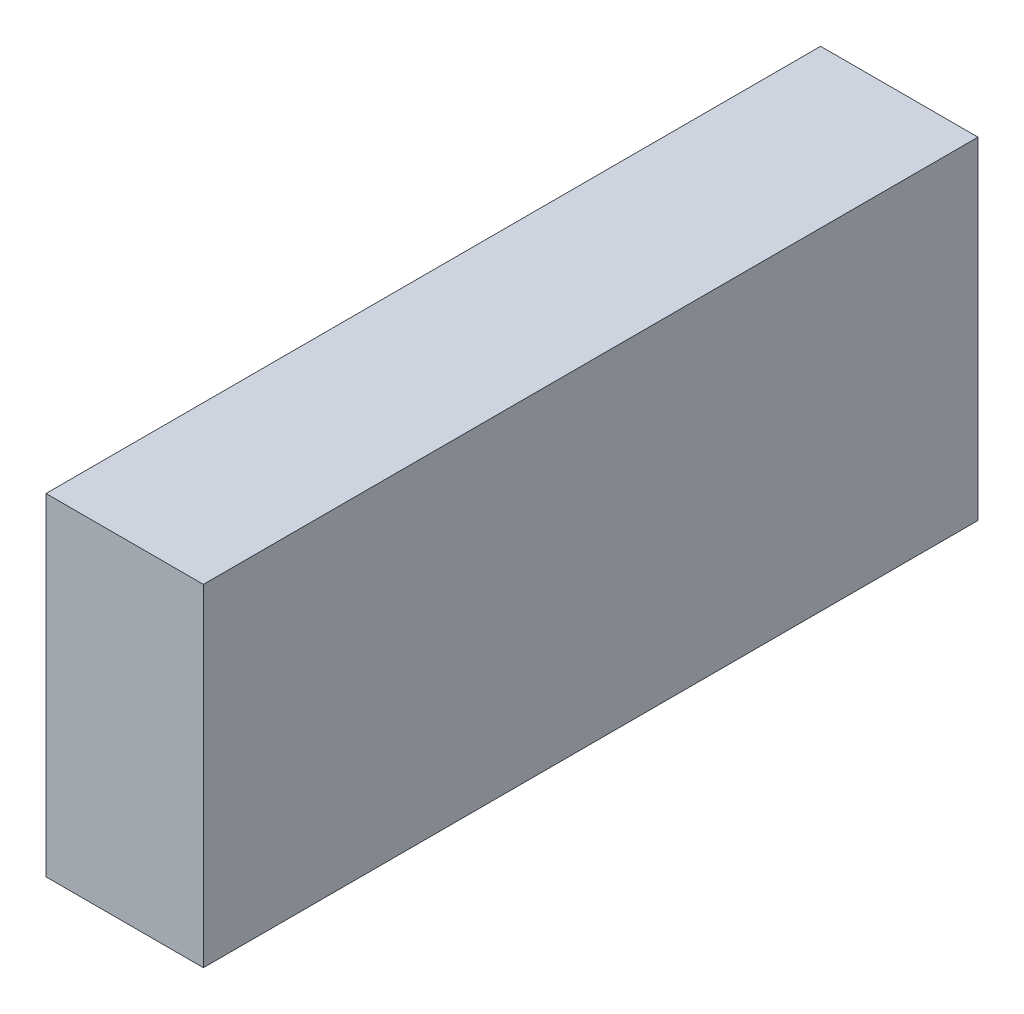
SolidWorks part; units mm, degrees
ref_plane "Alzado" through (0, 0, 0) normal (0, 0, 1) x (1, 0, 0)
ref_plane "Planta" through (0, 0, 0) normal (0, 1, 0) x (1, 0, 0)
ref_plane "Vista lateral" through (0, 0, 0) normal (1, 0, 0) x (0, 0, -1)
sketch "Croquis1" plane through (0, 0, 0) normal (0, 0, 1) x (1, 0, 0)
  line L1 (5.08, -10.715) -> (-5.08, -10.715)
  line L2 (5.08, -10.715) -> (5.08, 10.715)
  line L3 (5.08, 10.715) -> (-5.08, 10.715)
  line L4 (-5.08, -10.715) -> (-5.08, 10.715)
  line L5 (5.08, -10.715) -> (-5.08, 10.715) construction
  line L6 (5.08, 10.715) -> (-5.08, -10.715) construction
  point P0 (0, 0)
  dimension "D1" = 10.16
  dimension "D2" = 21.43
extrude "Saliente-Extruir1" add sketch "Croquis1" along normal mid plane 50
